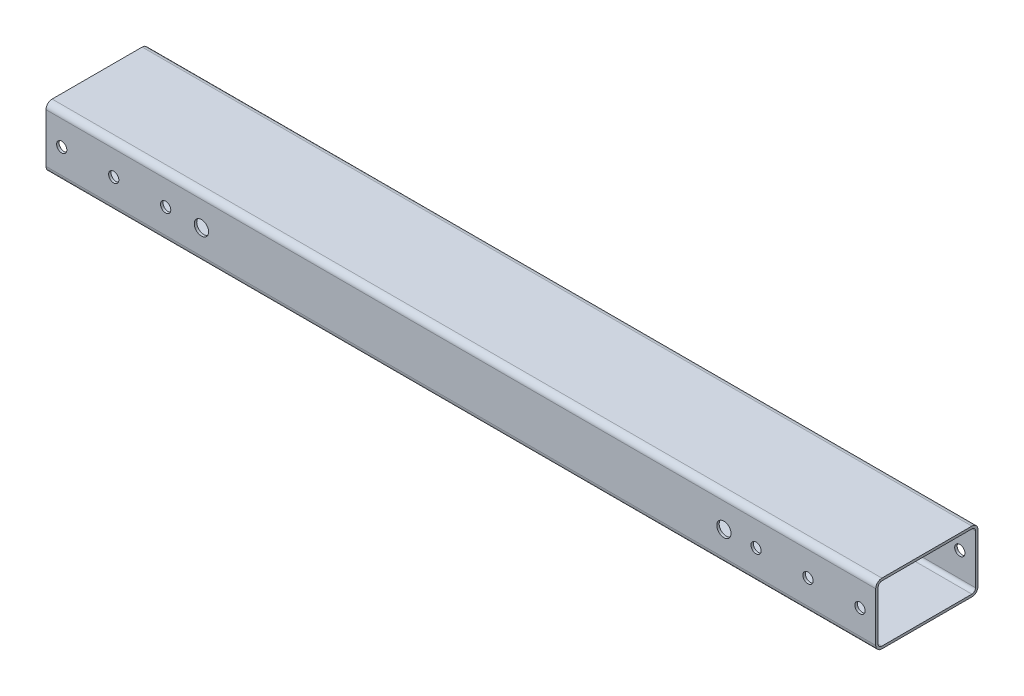
SolidWorks part; units mm, degrees
material "AISI 304"
ref_plane "Plano frontal" through (0, 0, 0) normal (0, 0, 1) x (1, 0, 0)
ref_plane "Plano superior" through (0, 0, 0) normal (0, 1, 0) x (1, 0, 0)
ref_plane "Plano direito" through (0, 0, 0) normal (1, 0, 0) x (0, 0, -1)
sketch "Esboço1" plane through (0, 0, 0) normal (0, 0, 1) x (1, 0, 0)
  line L0 (0, 0) -> (405.6, 0)
  dimension "D1" = 405.6
other "Tubo retangular 50 X 30 X 2.6(1)"
ref_plane "Plano1" through (0, 0, 0) normal (1, 0, 0) x (0, 1, 0)
sketch "Sketch1" plane through (0, 0, 0) normal (1, 0, 0) x (0, 1, 0)
  line L0 (-12, -23.8) -> (12, -23.8)
  line L1 (-13.8, -22) -> (-13.8, 22)
  line L2 (12, 23.8) -> (-12, 23.8)
  line L3 (13.8, 22) -> (13.8, -22)
  line L4 (-12, -25) -> (12, -25)
  line L5 (-15, -22) -> (-15, 22)
  line L6 (12, 25) -> (-12, 25)
  line L7 (15, 22) -> (15, -22)
  arc A0 (15, 22) -> (12, 25) centre (12, 22) ccw
  arc A1 (12, -25) -> (15, -22) centre (12, -22) ccw
  arc A2 (-15, -22) -> (-12, -25) centre (-12, -22) ccw
  arc A3 (-12, 25) -> (-15, 22) centre (-12, 22) ccw
  arc A4 (-12, 23.8) -> (-13.8, 22) centre (-12, 22) ccw
  arc A5 (13.8, 22) -> (12, 23.8) centre (12, 22) ccw
  arc A6 (12, -23.8) -> (13.8, -22) centre (12, -22) ccw
  arc A7 (-13.8, -22) -> (-12, -23.8) centre (-12, -22) ccw
  point P0 (0, 25)
  point P1 (15, 0)
  point P2 (0, -25)
  point P3 (-15, 0)
  point P4 (-15, 25)
  point P5 (15, 25)
  point P6 (15, -25)
  point P7 (-15, -25)
  point P8 (0, 0)
  point P33 (0, 0)
  dimension "D1" = 3
  dimension "Thickness" = 1.2
  dimension "V_leg" = 50
  dimension "H_leg" = 30
sketch "Esboço2" plane through (0, 0, -25) normal (0, 0, -1) x (-1, 0, 0)
  line L0 (0, -12) -> (0, 12) construction
  line L1 (-58.5, 0) -> (-33.1, 0) construction
  line L2 (-33.1, 0) -> (-7.7, 0) construction
  line L3 (-7.7, 0) -> (0, 0) construction
  line L4 (-202.8, 15) -> (-202.8, -15) construction
  line L5 (-405.6, 15) -> (0, 15) construction
  line L6 (-405.6, -15) -> (0, -15) construction
  line L7 (-397.9, 0) -> (-405.6, 0) construction
  line L8 (-372.5, 0) -> (-397.9, 0) construction
  line L9 (-347.1, 0) -> (-372.5, 0) construction
  circle A0 centre (-58.5, 0) radius 2.5
  circle A1 centre (-33.1, 0) radius 2.5
  circle A2 centre (-7.7, 0) radius 2.5
  circle A6 centre (-397.9, 0) radius 2.5
  circle A7 centre (-372.5, 0) radius 2.5
  circle A8 centre (-347.1, 0) radius 2.5
  dimension "D1" = 7.7
  dimension "D2" = 25.4
  dimension "D3" = 25.4
  dimension "D4" = 5
  dimension "D5" = 5
  dimension "D6" = 5
extrude "Corte-extrusão1" cut sketch "Esboço2" against normal through all
sketch "Esboço3" plane through (0, 0, 25) normal (0, 0, 1) x (1, 0, 0)
  circle A0 centre (75.9847, 0) radius 3.5
  circle A1 centre (331.3847, 0) radius 3.5
extrude "Corte-extrusão2" cut sketch "Esboço3" against normal through all
